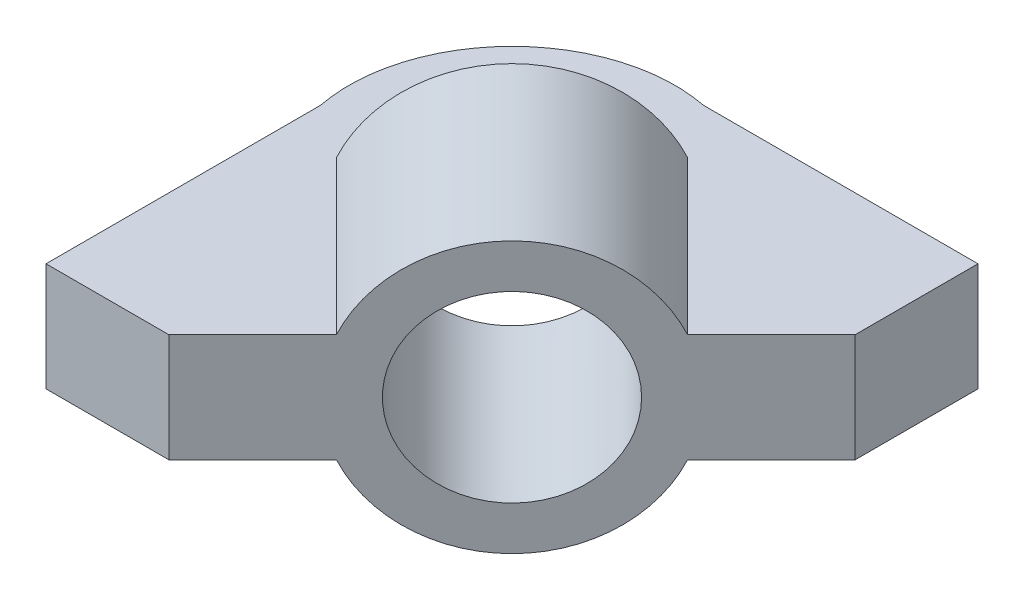
SolidWorks part; units mm, degrees
material "ABS"
ref_plane "Front Plane" through (0, 0, 0) normal (0, 0, 1) x (1, 0, 0)
ref_plane "Top Plane" through (0, 0, 0) normal (0, 1, 0) x (1, 0, 0)
ref_plane "Right Plane" through (0, 0, 0) normal (1, 0, 0) x (0, 0, -1)
sketch "Sketch1" plane through (0, 0, 0) normal (0, 1, 0) x (1, 0, 0)
  line L0 (0, 0) -> (20.5, 0) construction
  line L1 (20.5, 0) -> (20.5, -1.5)
  line L2 (20.5, -1.5) -> (1.5, -20.5)
  line L3 (1.5, -20.5) -> (0, -20.5)
  line L4 (0, -20.5) -> (0, 0) construction
  line L5 (7.0711, 0) -> (0, -7.0711) construction
  line L6 (-3.5355, -3.5355) -> (3.5355, 3.5355) construction
  line L7 (-3.5355, -3.5355) -> (0, -7.0711) construction
  line L8 (3.5355, 3.5355) -> (7.0711, 0) construction
  line L9 (-3.5355, -3.5355) -> (-3.5355, -20.5) construction
  line L10 (-3.5355, -20.5) -> (-2.0355, -20.5)
  line L11 (-2.0355, -20.5) -> (-2.0355, -5.0355) construction
  line L12 (3.5355, 3.5355) -> (20.5, 3.5355)
  line L13 (20.5, 3.5355) -> (20.5, 2.0355)
  line L14 (20.5, 2.0355) -> (5.0355, 2.0355) construction
  line L15 (0, -7.0711) -> (7.4645, -14.5355) construction
  line L16 (7.0711, 0) -> (14.5355, -7.4645) construction
  line L17 (-2.0355, -20.5) -> (-2.0355, -10.5) construction
  line L18 (-2.0355, -10.5) -> (-3.5355, -10.5) construction
  line L19 (-5.3033, -5.3033) -> (5.3033, 5.3033) construction
  line L20 (-5.3033, -5.3033) -> (-5.3033, -20.5)
  line L21 (-5.3033, -20.5) -> (-3.5355, -20.5)
  line L22 (5.3033, 5.3033) -> (20.5, 5.3033)
  line L23 (20.5, 5.3033) -> (20.5, 3.5355)
  line L24 (-5.3033, -5.3033) -> (5.6967, -16.3033) construction
  line L25 (5.3033, 5.3033) -> (16.3033, -5.6967) construction
  line L26 (-3.5355, -20.5) -> (-3.5355, -15) construction
  line L27 (-3.5355, -16.5) -> (-3.5355, -13.5) construction
  line L28 (-5.3033, -13.5) -> (6.4289, -13.5) construction
  line L29 (6.4289, -13.5) -> (6.4289, -16.5) construction
  line L30 (6.4289, -16.5) -> (-5.3033, -16.5) construction
  line L31 (-2.0355, -20.5) -> (0, -20.5)
  line L32 (20.5, 2.0355) -> (20.5, 0)
  line L33 (0, 0) -> (-2.8284, 2.8284) construction
  line L34 (-2.8284, 2.8284) -> (-8.1317, -2.4749) construction
  line L35 (-8.1317, -2.4749) -> (-5.3033, -5.3033) construction
  line L36 (-2.8284, 2.8284) -> (2.4749, 8.1317) construction
  line L37 (2.4749, 8.1317) -> (5.3033, 5.3033) construction
  arc A0 (-5.3033, -5.3033) -> (5.3033, 5.3033) centre (3.5576, -3.5576) cw
  point P11 (0, 0)
  point P24 (0, 0)
  point P31 (-3.5355, -15)
  point P39 (0, 0)
  point P40 (0, 0)
  dimension "D1" = 20.5
  dimension "D2" = 20.5
  dimension "D3" = 1.5
  dimension "D4" = 1.5
  dimension "D5" = 10
  dimension "D6" = 45
  dimension "D7" = 10
  dimension "D8" = 1.5
  dimension "D9" = 1.5
  dimension "D10" = 10
  dimension "D11" = 15
  dimension "D12" = 5.5
  dimension "D13" = 3
  dimension "D14" = 4
extrude "Boss-Extrude1" add sketch "Sketch1" along normal mid plane 6
sketch "Sketch2" plane through (11, 0, 11) normal (0.7071, 0, 0.7071) x (0.7071, 0, -0.7071)
  circle A0 centre (0, 0) radius 5.075
  circle A1 centre (0, 0) radius 7.5
  dimension "D1" = 15
  dimension "D2" = 10.15
extrude "Boss-Extrude2" add sketch "Sketch2" against normal blind 12.02
sketch "Sketch3" plane through (11, 0, 11) normal (0.7071, 0, 0.7071) x (0.7071, 0, -0.7071)
  circle A0 centre (0, 0) radius 5.075
  dimension "D1" = 10.15
extrude "Cut-Extrude1" cut sketch "Sketch3" against normal blind 12.02
sketch "Sketch4" plane through (0, 3, 0) normal (0, 1, 0) x (1, 0, 0)
  line L0 (-5.651, -4.9439) -> (4.9513, 5.6584) construction
  circle A0 centre (-0.3498, 0.3573) radius 1.5
  arc A1 (5.3033, 5.3033) -> (-5.3033, -5.3033) centre (3.5576, -3.5576) ccw construction
  point P5 (-2.8284, 2.8284)
  dimension "D1" = 3
  dimension "D2" = 3.5
extrude "Cut-Extrude2" cut sketch "Sketch4" against normal up to surface (6 mm away) up to face at (5.5309, -3, 5.5309)
sketch "Sketch5" plane through (-5.3033, 0, 0) normal (-1, 0, 0) x (0, 0, 1)
  line L0 (20.5, 0) -> (5.3033, 0) construction
  line L1 (20.5, 3) -> (20.5, -3) construction
  line L3 (5.3033, 3) -> (5.3033, -3) construction
  circle A0 centre (15, 0) radius 1.5
  point P4 (0, 0)
  dimension "D2" = 3
  dimension "D1" = 5.5
extrude "Cut-Extrude3" cut sketch "Sketch5" against normal blind 3
sketch "Sketch6" plane through (0, 0, -5.3033) normal (0, 0, -1) x (-1, 0, 0)
  line L0 (-20.5, 0) -> (-5.3033, 0) construction
  line L1 (-20.5, 3) -> (-20.5, -3) construction
  line L2 (-5.3033, 3) -> (-5.3033, -3) construction
  circle A0 centre (-15, 0) radius 1.5
  dimension "D2" = 3
  dimension "D1" = 5.5
extrude "Cut-Extrude4" cut sketch "Sketch6" against normal blind 3
